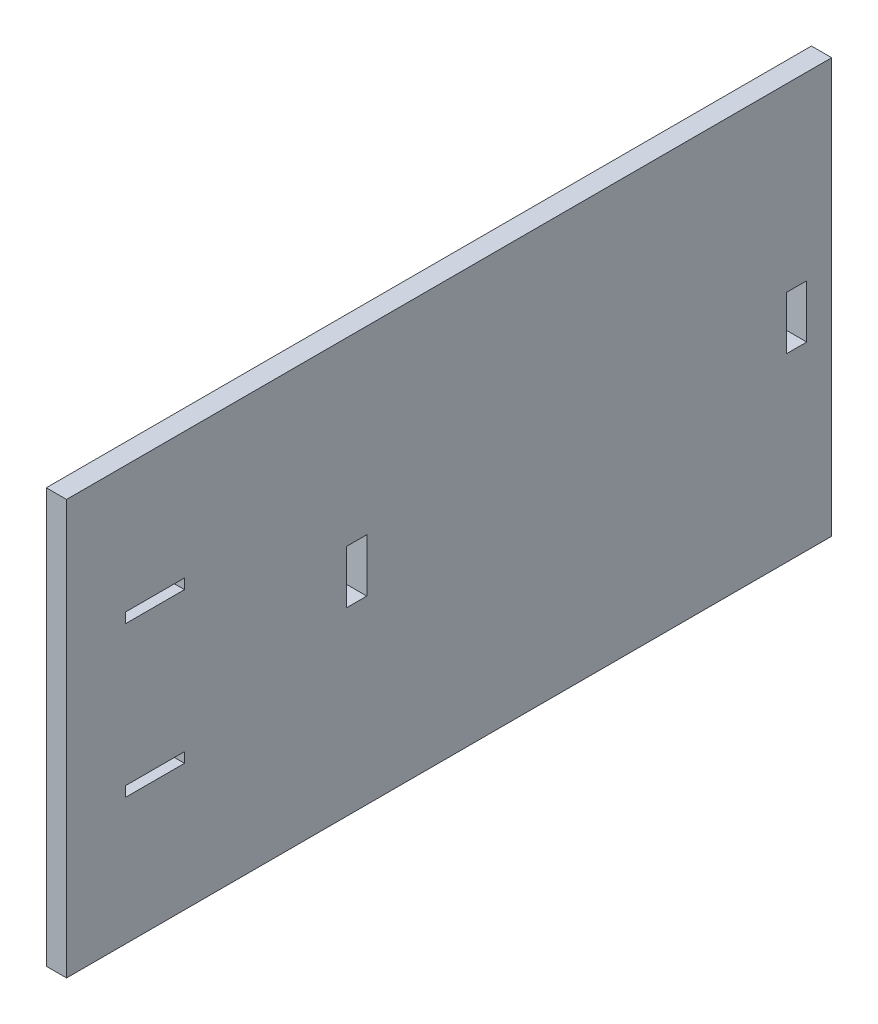
SolidWorks part; units mm, degrees
ref_plane "Front Plane" through (0, 0, 0) normal (0, 0, 1) x (1, 0, 0)
ref_plane "Top Plane" through (0, 0, 0) normal (0, 1, 0) x (1, 0, 0)
ref_plane "Right Plane" through (0, 0, 0) normal (1, 0, 0) x (0, 0, -1)
sketch "Sketch1" plane through (0, 0, 0) normal (1, 0, 0) x (0, 0, -1)
  line L0 (94.175, 73.33) -> (87.825, 73.33) construction
  line L1 (0, 0) -> (240, 0)
  line L2 (0, 0) -> (0, 130)
  line L3 (0, 130) -> (240, 130)
  line L4 (240, 0) -> (240, 130)
  line L5 (94.175, 73.33) -> (94.175, 56.6633) construction
  line L6 (87.825, 73.33) -> (87.825, 56.6633) construction
  line L7 (94.175, 56.6633) -> (87.825, 56.6633) construction
  line L8 (232.175, 73.3367) -> (225.825, 73.3367) construction
  line L9 (225.825, 73.3367) -> (225.825, 56.67) construction
  line L10 (232.175, 73.3367) -> (232.175, 56.67) construction
  line L11 (232.175, 56.67) -> (225.825, 56.67) construction
  line L12 (94.175, 73.33) -> (87.825, 73.33)
  line L13 (94.175, 73.33) -> (94.175, 56.6633)
  line L14 (87.825, 73.33) -> (87.825, 56.6633)
  line L15 (94.175, 56.6633) -> (87.825, 56.6633)
  line L16 (232.175, 73.3367) -> (225.825, 73.3367)
  line L17 (225.825, 73.3367) -> (225.825, 56.67)
  line L18 (232.175, 73.3367) -> (232.175, 56.67)
  line L19 (232.175, 56.67) -> (225.825, 56.67)
  line L20 (0, 65) -> (37, 65) construction
  line L21 (37, 65) -> (37, 43) construction
  line L22 (37, 87) -> (18.5, 87)
  line L23 (37, 87) -> (37, 90.175)
  line L24 (37, 90.175) -> (18.5, 90.175)
  line L25 (18.5, 87) -> (18.5, 90.175)
  line L26 (37, 43) -> (18.5, 43)
  line L27 (37, 43) -> (37, 39.825)
  line L28 (37, 39.825) -> (18.5, 39.825)
  line L29 (18.5, 43) -> (18.5, 39.825)
  line L30 (37, 65) -> (37, 87) construction
  point P23 (30.9897, 57.5514)
  dimension "D1" = 130
  dimension "D2" = 240
  dimension "D3" = 18.5
  dimension "D4" = 18.5
  dimension "D5" = 44
  dimension "D6" = 3.175
  dimension "D7" = 3.175
  dimension "D8" = 37
extrude "Boss-Extrude1" add sketch "Sketch1" along normal blind 6.35
